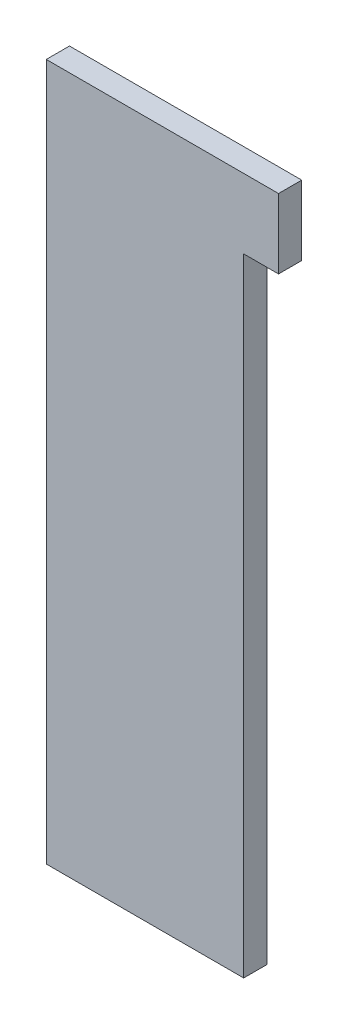
SolidWorks part; units mm, degrees
ref_plane "Front Plane" through (0, 0, 0) normal (0, 0, 1) x (1, 0, 0)
ref_plane "Top Plane" through (0, 0, 0) normal (0, 1, 0) x (1, 0, 0)
ref_plane "Right Plane" through (0, 0, 0) normal (1, 0, 0) x (0, 0, -1)
sketch "Sketch1" plane through (0, 0, 0) normal (0, 0, 1) x (1, 0, 0)
  line L1 (0, 0) -> (17, 0)
  line L2 (0, 0) -> (0, 60)
  line L3 (0, 60) -> (16.5672, 60)
  line L4 (17, 0) -> (17, 54)
  line L5 (16.5672, 60) -> (20, 60)
  line L7 (17, 54) -> (20, 54)
  line L8 (20, 60) -> (20, 54)
  point P8 (0, 0)
  point P9 (0, 0)
  dimension "D1" = 20
  dimension "D2" = 60
  dimension "D3" = 6
  dimension "D4" = 17
extrude "Boss-Extrude1" add sketch "Sketch1" along normal blind 2
